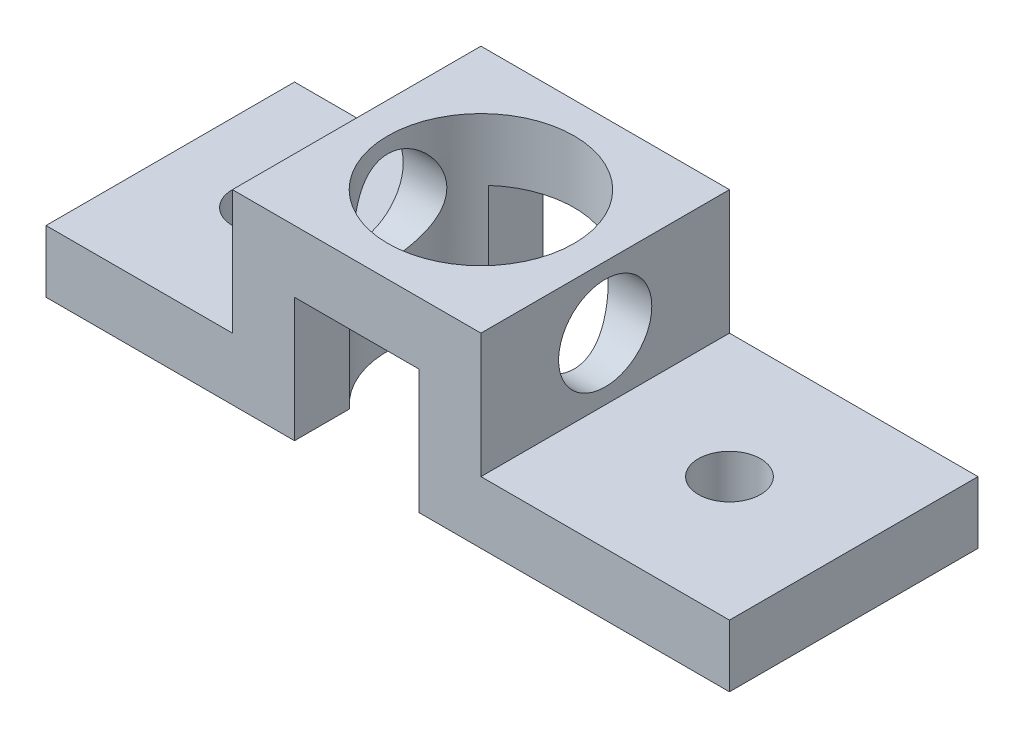
SolidWorks part; units mm, degrees
material "6061 Alloy"
ref_plane "Front" through (0, 0, 0) normal (0, 0, 1) x (1, 0, 0)
ref_plane "Top" through (0, 0, 0) normal (0, 1, 0) x (1, 0, 0)
ref_plane "Right" through (0, 0, 0) normal (1, 0, 0) x (0, 0, -1)
sketch "Sketch1" plane through (0, 0, 0) normal (0, 0, 1) x (1, 0, 0)
  line L0 (0, 0) -> (25.4, 0)
  line L1 (25.4, 0) -> (25.4, 12.7)
  line L2 (25.4, 12.7) -> (38.1, 12.7)
  line L3 (38.1, 12.7) -> (38.1, 0)
  line L4 (38.1, 0) -> (69.85, 0)
  line L5 (69.85, 0) -> (69.85, 6.35)
  line L6 (69.85, 6.35) -> (44.45, 6.35)
  line L7 (44.45, 6.35) -> (44.45, 19.05)
  line L8 (44.45, 19.05) -> (19.05, 19.05)
  line L9 (19.05, 19.05) -> (19.05, 6.35)
  line L10 (19.05, 6.35) -> (0, 6.35)
  line L11 (0, 6.35) -> (0, 0)
  line L12 (31.75, -4.4588) -> (31.75, 32.4648) construction
  dimension "D1" = 25.4
  dimension "D2" = 12.7
  dimension "D3" = 31.75
  dimension "D4" = 6.35
  dimension "D5" = 12.7
  dimension "D6" = 19.05
  dimension "D7" = 12.7
  dimension "D8" = 19.05
  dimension "D9" = 44.45
extrude "Boss-Extrude1" add sketch "Sketch1" along normal blind 25.4
hole_wizard "1/2 (0.75) Diameter Hole2" positions "Sketch5" profile "Sketch6" hole size "1/2" standard "ANSI Inch" end condition through all
sketch "Sketch5" plane through (0, 19.05, 0) normal (0, 1, 0) x (1, 0, 0)
  line L0 (44.45, -25.4) -> (44.45, 0) construction
  line L1 (44.45, -25.4) -> (19.05, -25.4) construction
  point P0 (31.75, -12.7)
  dimension "D1" = 12.7
  dimension "D2" = 12.7
sketch "Sketch6" plane through (31.75, 19.05, 12.7) normal (1, 0, 0) x (0, 0, 1)
  line L0 (0, 0) -> (0, 19.05)
  line L1 (0, 19.05) -> (9.525, 19.05)
  line L2 (9.525, 19.05) -> (9.525, 0)
  line L5 (9.525, 0) -> (0, 0)
  line L11 (0, -6.35) -> (0, 107.95) construction
  dimension "Thru Hole Dia." = 19.05
  dimension "Thru Hole Depth" = 19.05
hole_wizard "1/2 (0.25) Diameter Hole1" positions "Sketch7" profile "Sketch8" hole size "1/2" standard "ANSI Inch" end condition through all
sketch "Sketch7" plane through (0, 6.35, 0) normal (0, 1, 0) x (1, 0, 0)
  line L0 (19.05, -25.4) -> (0, -25.4) construction
  line L2 (19.05, -25.4) -> (19.05, 0) construction
  point P0 (9.525, -12.7)
  dimension "D1" = 12.7
  dimension "D2" = 9.525
sketch "Sketch8" plane through (9.525, 6.35, 12.7) normal (1, 0, 0) x (0, 0, 1)
  line L0 (0, 0) -> (0, 6.35)
  line L1 (0, 6.35) -> (3.175, 6.35)
  line L2 (3.175, 6.35) -> (3.175, 0)
  line L5 (3.175, 0) -> (0, 0)
  line L11 (0, -6.35) -> (0, 107.95) construction
  dimension "Thru Hole Dia." = 6.35
  dimension "Thru Hole Depth" = 6.35
hole_wizard "1/2 (0.25) Diameter Hole2" positions "Sketch9" profile "Sketch10" hole size "1/2" standard "ANSI Inch" end condition through all
sketch "Sketch9" plane through (0, 6.35, 0) normal (0, 1, 0) x (1, 0, 0)
  line L0 (69.85, -25.4) -> (44.45, -25.4) construction
  line L1 (44.45, -25.4) -> (44.45, 0) construction
  point P0 (57.15, -12.7)
  dimension "D1" = 12.7
  dimension "D2" = 12.7
sketch "Sketch10" plane through (57.15, 6.35, 12.7) normal (1, 0, 0) x (0, 0, 1)
  line L0 (0, 0) -> (0, 6.35)
  line L1 (0, 6.35) -> (3.175, 6.35)
  line L2 (3.175, 6.35) -> (3.175, 0)
  line L5 (3.175, 0) -> (0, 0)
  line L11 (0, -6.35) -> (0, 107.95) construction
  dimension "Thru Hole Dia." = 6.35
  dimension "Thru Hole Depth" = 6.35
hole_wizard "1/2 (0.375) Diameter Hole1" positions "Sketch11" profile "Sketch12" hole size "1/2" standard "ANSI Inch" end condition through all
sketch "Sketch11" plane through (44.45, 0, 0) normal (1, 0, 0) x (0, 0, -1)
  line L0 (-25.4, 0) -> (0, 0) construction
  line L1 (-25.4, 6.35) -> (-25.4, 19.05) construction
  point P0 (-12.7, 12.7)
  dimension "D1" = 12.7
  dimension "D2" = 12.7
sketch "Sketch12" plane through (44.45, 12.7, 12.7) normal (0, 1, 0) x (0, 0, -1)
  line L0 (0, 0) -> (0, 44.45)
  line L1 (0, 44.45) -> (4.7625, 44.45)
  line L2 (4.7625, 44.45) -> (4.7625, 0)
  line L5 (4.7625, 0) -> (0, 0)
  line L11 (0, -6.35) -> (0, 107.95) construction
  dimension "Thru Hole Dia." = 9.525
  dimension "Thru Hole Depth" = 44.45
